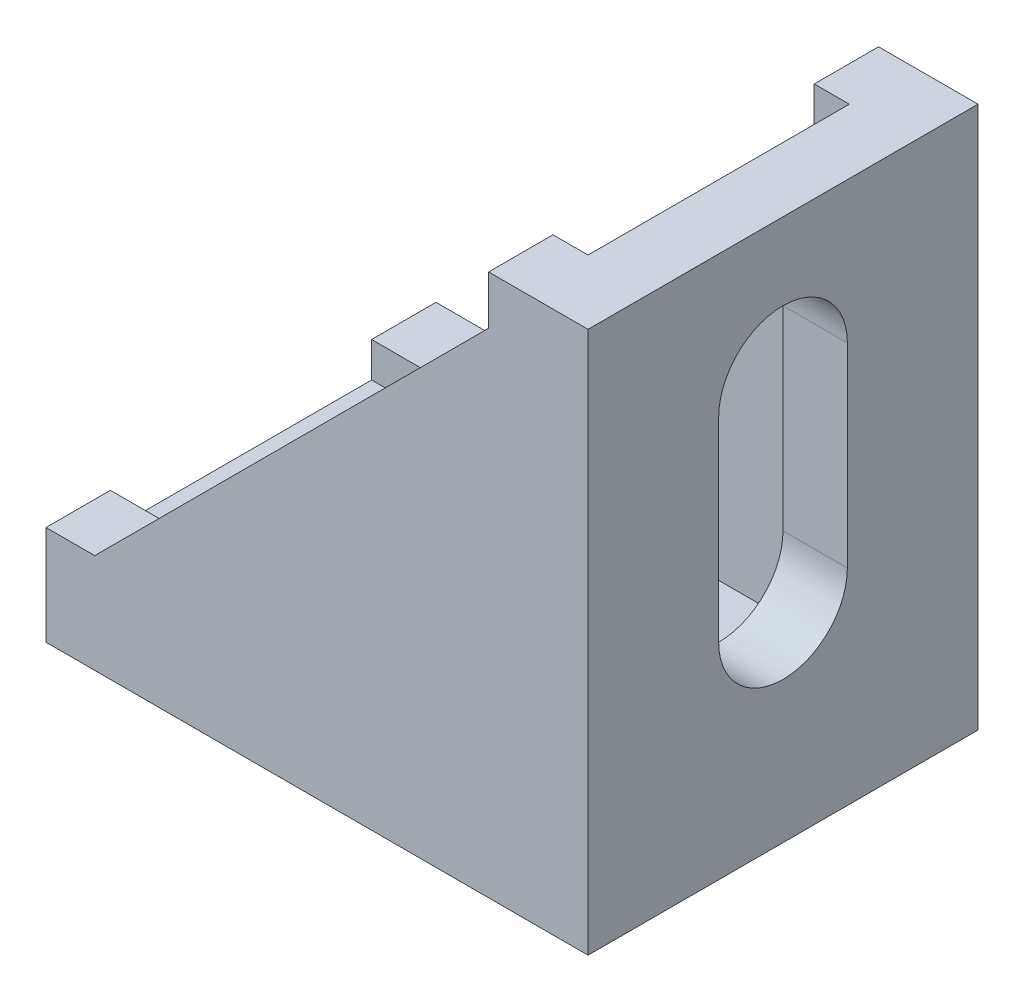
SolidWorks part; units mm, degrees
ref_plane "前视基准面" through (0, 0, 0) normal (0, 0, 1) x (1, 0, 0)
ref_plane "上视基准面" through (0, 0, 0) normal (0, 1, 0) x (1, 0, 0)
ref_plane "右视基准面" through (0, 0, 0) normal (1, 0, 0) x (0, 0, -1)
sketch "草图2" plane through (0, 0, 0) normal (0, 1, 0) x (1, 0, 0)
  line L1 (-13.9, 10) -> (13.9, 10)
  line L2 (-13.9, 10) -> (-13.9, -10)
  line L3 (-13.9, -10) -> (13.9, -10)
  line L4 (13.9, 10) -> (13.9, -10)
  line L5 (-13.9, 10) -> (13.9, -10) construction
  line L6 (-13.9, -10) -> (13.9, 10) construction
  point P0 (0, 0)
extrude "凸台-拉伸1" add sketch "草图2" along normal blind 3.3
sketch "草图4" plane through (0, 3.3, 0) normal (0, 1, 0) x (1, 0, 0)
  line L0 (-13.9, 10) -> (-13.9, 6.7)
  line L1 (-13.9, 10) -> (-13.9, -10) construction
  line L2 (-13.9, 6.7) -> (10.6, 6.7)
  line L3 (10.6, 6.7) -> (10.6, -6.7)
  line L4 (10.6, -6.7) -> (-13.9, -6.7)
  line L5 (-13.9, -6.7) -> (-13.9, -10)
  line L6 (-13.9, -10) -> (13.9, -10)
  line L7 (13.9, -10) -> (13.9, 10)
  line L8 (13.9, 10) -> (-13.9, 10)
extrude "凸台-拉伸2" add sketch "草图4" along normal blind 24.5
sketch "草图5" plane through (0, 0, 10) normal (0, 0, 1) x (1, 0, 0)
  line L0 (8.8015, 27.8) -> (8.8015, 25.3)
  line L1 (-13.9, 27.8) -> (13.9, 27.8) construction
  line L2 (-13.9, 5.0985) -> (-13.9, 27.8)
  line L3 (-13.9, 5.0985) -> (-11.4, 5.0985)
  line L4 (-11.4, 5.0985) -> (8.8015, 25.3)
  line L5 (-13.9, 27.8) -> (8.8015, 27.8)
extrude "切除-拉伸1" cut sketch "草图5" against normal blind 24.8
sketch "草图6" plane through (10.6, 0, 0) normal (-1, 0, 0) x (0, 0, 1)
  line L0 (-3.3, 20.55) -> (-3.3, 10.55)
  line L1 (3.3, 20.55) -> (3.3, 10.55)
  arc A0 (3.3, 20.55) -> (-3.3, 20.55) centre (0, 20.55) ccw
  arc A1 (-3.3, 10.55) -> (3.3, 10.55) centre (0, 10.55) ccw
  point P8 (0, 15.55)
extrude "切除-拉伸2" cut sketch "草图6" against normal blind 24.8
sketch "草图7" plane through (0, 3.3, 0) normal (0, 1, 0) x (1, 0, 0)
  line L0 (3.35, 3.3) -> (-6.65, 3.3)
  line L1 (3.35, -3.3) -> (-6.65, -3.3)
  arc A0 (3.35, -3.3) -> (3.35, 3.3) centre (3.35, 0) ccw
  arc A1 (-6.65, 3.3) -> (-6.65, -3.3) centre (-6.65, 0) ccw
extrude "切除-拉伸3" cut sketch "草图7" against normal blind 24.8
